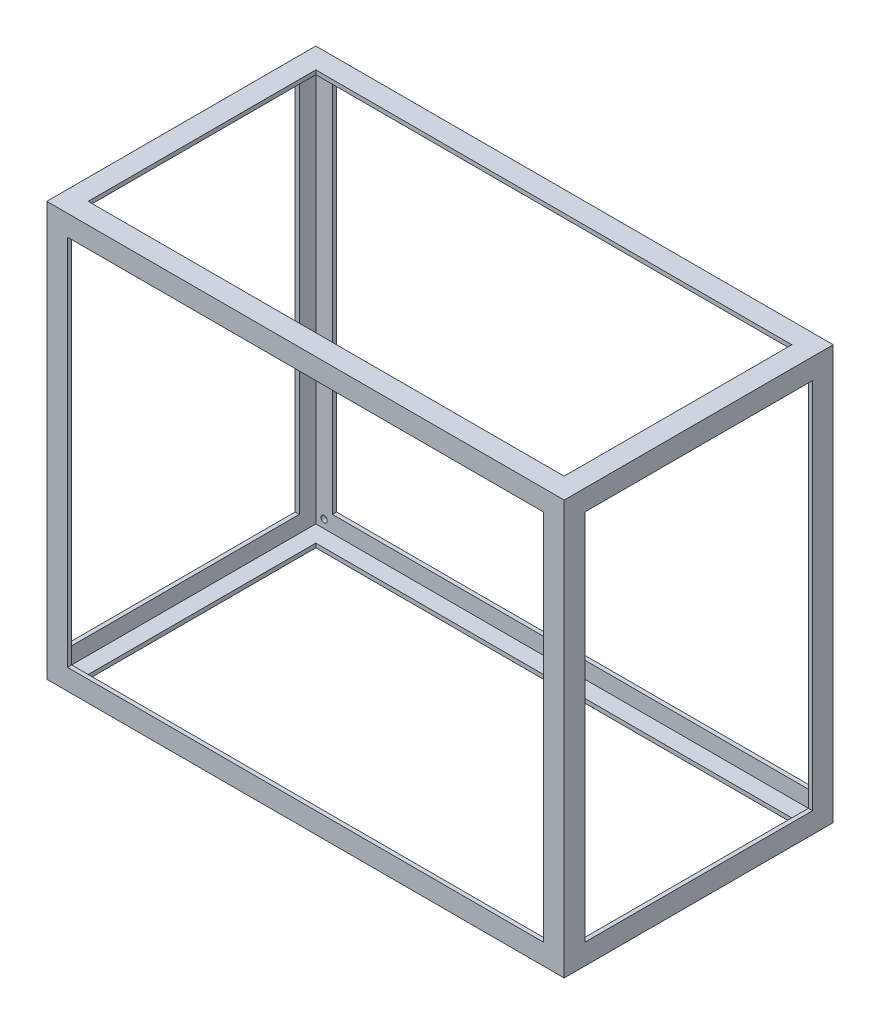
SolidWorks part; units mm, degrees
ref_plane "Front Plane" through (0, 0, 0) normal (0, 0, 1) x (1, 0, 0)
ref_plane "Top Plane" through (0, 0, 0) normal (0, 1, 0) x (1, 0, 0)
ref_plane "Right Plane" through (0, 0, 0) normal (1, 0, 0) x (0, 0, -1)
sketch "Sketch1" plane through (0, 0, 0) normal (0, 1, 0) x (1, 0, 0)
  line L1 (-125, 65) -> (125, 65)
  line L2 (-125, 65) -> (-125, -65)
  line L3 (-125, -65) -> (125, -65)
  line L4 (125, 65) -> (125, -65)
  line L5 (-125, 65) -> (125, -65) construction
  line L6 (-125, -65) -> (125, 65) construction
  point P0 (0, 0)
  dimension "D1" = 130
  dimension "D2" = 250
extrude "Boss-Extrude1" add sketch "Sketch1" along normal blind 200
sketch "Sketch2" plane through (0, 200, 0) normal (0, 1, 0) x (1, 0, 0)
  line L0 (-125, 65) -> (-125, -65) construction
  line L1 (-123, 63) -> (123, 63)
  line L2 (-123, 63) -> (-123, -63)
  line L3 (-123, -63) -> (123, -63)
  line L4 (123, 63) -> (123, -63)
  line L5 (-123, 63) -> (123, -63) construction
  line L6 (-123, -63) -> (123, 63) construction
  line L7 (125, 65) -> (-125, 65) construction
  point P0 (0, 0)
  dimension "D1" = 2
  dimension "D2" = 2
extrude "Cut-Extrude1" cut sketch "Sketch2" against normal blind 198
sketch "Sketch3" plane through (0, 0, 65) normal (0, 0, 1) x (1, 0, 0)
  line L0 (-125, 200) -> (-125, 0) construction
  line L1 (-115, 190) -> (115, 190)
  line L2 (-115, 190) -> (-115, 10)
  line L3 (-115, 10) -> (115, 10)
  line L4 (115, 190) -> (115, 10)
  line L5 (-125, 0) -> (125, 0) construction
  line L6 (125, 200) -> (125, 0) construction
  line L7 (-125, 200) -> (125, 200) construction
  dimension "D1" = 10
  dimension "D2" = 10
  dimension "D3" = 10
  dimension "D4" = 10
extrude "Cut-Extrude2" cut sketch "Sketch3" against normal blind 3
sketch "Sketch4" plane through (0, 0, 65) normal (0, 0, 1) x (1, 0, 0)
  line L0 (125, 200) -> (125, 0) construction
  line L1 (-125, 200) -> (125, 200)
  line L2 (-125, 200) -> (-125, 198)
  line L3 (-125, 198) -> (125, 198)
  line L4 (125, 200) -> (125, 198)
  dimension "D1" = 2
extrude "Boss-Extrude2" add sketch "Sketch4" against normal blind 10
sketch "Sketch5" plane through (125, 0, 0) normal (1, 0, 0) x (0, 0, -1)
  line L0 (-65, 200) -> (-65, 0) construction
  line L1 (-55, 190) -> (55, 190)
  line L2 (-55, 190) -> (-55, 10)
  line L3 (-55, 10) -> (55, 10)
  line L4 (55, 190) -> (55, 10)
  line L5 (-65, 0) -> (65, 0) construction
  line L6 (65, 200) -> (65, 0) construction
  line L7 (-65, 200) -> (65, 200) construction
  dimension "D1" = 10
  dimension "D2" = 10
  dimension "D3" = 10
  dimension "D4" = 10
extrude "Cut-Extrude3" cut sketch "Sketch5" against normal blind 3
sketch "Sketch6" plane through (125, 0, 0) normal (1, 0, 0) x (0, 0, -1)
  line L0 (65, 200) -> (65, 0) construction
  line L1 (-65, 200) -> (65, 200)
  line L2 (-65, 200) -> (-65, 198)
  line L3 (-65, 198) -> (65, 198)
  line L4 (65, 200) -> (65, 198)
  dimension "D1" = 2
extrude "Boss-Extrude3" add sketch "Sketch6" against normal blind 10
sketch "Sketch7" plane through (0, 0, -65) normal (0, 0, -1) x (-1, 0, 0)
  line L0 (-125, 200) -> (-125, 0) construction
  line L1 (-115, 190) -> (115, 190)
  line L2 (-115, 190) -> (-115, 10)
  line L3 (-115, 10) -> (115, 10)
  line L4 (115, 190) -> (115, 10)
  line L5 (-125, 0) -> (125, 0) construction
  line L6 (125, 200) -> (125, 0) construction
  line L7 (-125, 200) -> (125, 200) construction
  dimension "D1" = 10
  dimension "D2" = 10
  dimension "D3" = 10
  dimension "D4" = 10
extrude "Cut-Extrude4" cut sketch "Sketch7" against normal blind 3
sketch "Sketch8" plane through (0, 0, -65) normal (0, 0, -1) x (-1, 0, 0)
  line L0 (125, 200) -> (125, 0) construction
  line L1 (-125, 200) -> (125, 200)
  line L2 (-125, 200) -> (-125, 198)
  line L3 (-125, 198) -> (125, 198)
  line L4 (125, 200) -> (125, 198)
  dimension "D1" = 2
extrude "Boss-Extrude4" add sketch "Sketch8" against normal blind 10
sketch "Sketch9" plane through (-125, 0, 0) normal (-1, 0, 0) x (0, 0, 1)
  line L0 (-65, 200) -> (-65, 0) construction
  line L1 (-55, 190) -> (55, 190)
  line L2 (-55, 190) -> (-55, 10)
  line L3 (-55, 10) -> (55, 10)
  line L4 (55, 190) -> (55, 10)
  line L5 (-65, 0) -> (65, 0) construction
  line L6 (65, 200) -> (65, 0) construction
  line L7 (-65, 200) -> (65, 200) construction
  dimension "D1" = 10
  dimension "D2" = 10
  dimension "D3" = 10
  dimension "D4" = 10
extrude "Cut-Extrude5" cut sketch "Sketch9" against normal blind 3
sketch "Sketch10" plane through (-125, 0, 0) normal (-1, 0, 0) x (0, 0, 1)
  line L0 (65, 200) -> (65, 0) construction
  line L1 (-65, 200) -> (65, 200)
  line L2 (-65, 200) -> (-65, 198)
  line L3 (-65, 198) -> (65, 198)
  line L4 (65, 200) -> (65, 198)
  dimension "D1" = 2
extrude "Boss-Extrude5" add sketch "Sketch10" against normal blind 10
sketch "Sketch11" plane through (0, 0, 0) normal (0, -1, 0) x (1, 0, 0)
  line L0 (-125, -65) -> (-125, 65) construction
  line L1 (-115, 55) -> (115, 55)
  line L2 (-115, 55) -> (-115, -55)
  line L3 (-115, -55) -> (115, -55)
  line L4 (115, 55) -> (115, -55)
  line L5 (125, -65) -> (-125, -65) construction
  line L6 (125, 65) -> (125, -65) construction
  line L7 (-125, 65) -> (125, 65) construction
  dimension "D1" = 10
  dimension "D2" = 10
  dimension "D3" = 10
  dimension "D4" = 10
extrude "Cut-Extrude7" cut sketch "Sketch11" against normal blind 3
sketch "Sketch12" plane through (0, 0, -65) normal (0, 0, -1) x (-1, 0, 0)
  line L0 (-125, 200) -> (-125, 0) construction
  line L1 (-125, 200) -> (125, 200) construction
  line L2 (0, 174.7722) -> (0, -40.2251) construction
  line L3 (-159.1294, 100) -> (159.1469, 100) construction
  line L4 (-125, 0) -> (125, 0) construction
  circle A0 centre (-119, 194) radius 1.5
  circle A1 centre (119, 194) radius 1.5
  circle A2 centre (119, 6) radius 1.5
  circle A3 centre (-119, 6) radius 1.5
  dimension "D1" = 3
  dimension "D2" = 6
  dimension "D3" = 6
  dimension "D4" = 100
extrude "Cut-Extrude8" cut sketch "Sketch12" against normal blind 3
